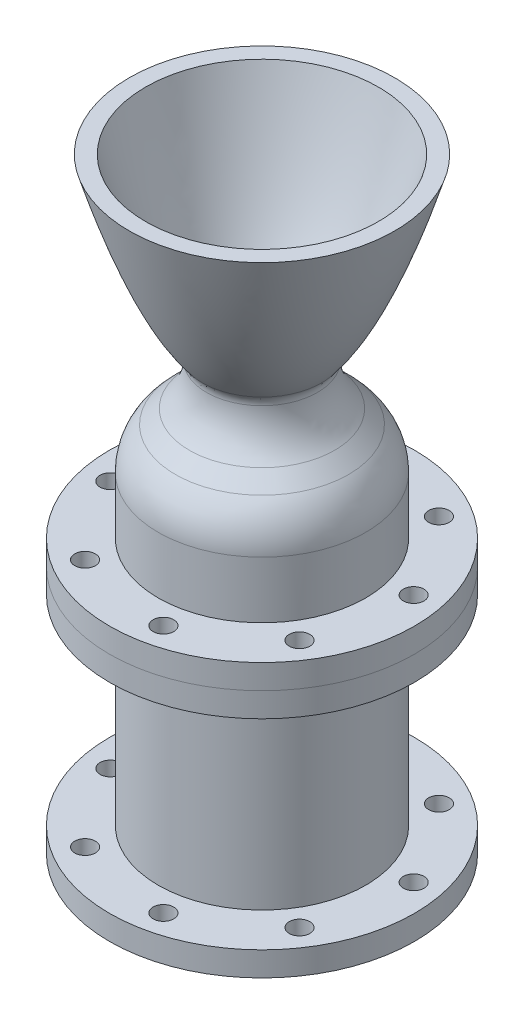
SolidWorks part; units mm, degrees
material "AISI 1020"
ref_plane "Front Plane" through (0, 0, 0) normal (0, 0, 1) x (1, 0, 0)
ref_plane "Top Plane" through (0, 0, 0) normal (0, 1, 0) x (1, 0, 0)
ref_plane "Right Plane" through (0, 0, 0) normal (1, 0, 0) x (0, 0, -1)
sketch "Sketch1" plane through (0, 0, 0) normal (0, 0, 1) x (1, 0, 0)
  line L0 (-0.0055, 165.816) -> (-0.0055, -134.6871) construction
  line L1 (71.7275, 109.9275) -> (81.7275, 109.9275)
  line L4 (53.8815, -59.7275) -> (53.8815, -262.9275)
  line L7 (63.8815, -59.761) -> (63.8815, -262.9447)
  line L8 (53.8815, -262.9275) -> (63.8815, -262.9447)
  spline S0 degree 2 poles (26.7953, 6.5094) (49.2614, 34.6361) (71.7275, 109.9275) knots 0 0 0 1 1 1 construction
  spline S1 degree 2 poles (26.7953, 6.5094) (49.2614, 34.6361) (71.7275, 109.9275) knots 0 0 0 1 1 1
  spline S2 degree 4 poles (24.1269, -0.7179) (24.126, -0.7018) (24.1243, -0.6738) (24.121, -0.6546) (24.115, -0.5166) (24.1058, -0.4369) (24.0994, -0.1066) (24.0979, 0.0018) (24.102, 0.2678) (24.1085, 0.4272) (24.1205, 0.6469) (24.1414, 0.9016) (24.1752, 1.2027) (24.2265, 1.5422) (24.2905, 1.8812) (24.3671, 2.2165) (24.4563, 2.5494) (24.5577, 2.8783) (24.6716, 3.2035) (24.7972, 3.5238) (24.9353, 3.8398) (25.0841, 4.1494) (25.246, 4.4549) (25.4165, 4.7515) (25.6025, 5.0459) (25.7918, 5.3257) (26.0044, 5.6109) (26.1789, 5.8331) (26.3663, 6.0501) (26.5046, 6.2088) (26.757, 6.4728) (26.837, 6.5526) (27.1016, 6.806) (27.1881, 6.8783) (27.2854, 6.9667) (27.3038, 6.9803) (27.3264, 7.0004) knots 0 0 0 0 0 0.005192 0.010384 0.020768 0.041536 0.082569 0.102427 0.122284 0.142142 0.162 0.201716 0.241431 0.281147 0.320863 0.360578 0.400294 0.44001 0.479725 0.519441 0.559156 0.598872 0.638588 0.678303 0.718019 0.757735 0.79745 0.837166 0.857024 0.876882 0.916597 0.958047 0.979024 0.989512 1 1 1 1 1 construction
  spline S3 degree 4 poles (24.0991, 0.0002) (24.0991, 0.0361) (24.0996, 0.1103) (24.102, 0.2678) (24.1085, 0.4272) (24.1205, 0.6469) (24.1414, 0.9016) (24.1752, 1.2027) (24.2265, 1.5422) (24.2905, 1.8812) (24.3671, 2.2165) (24.4563, 2.5494) (24.5577, 2.8783) (24.6716, 3.2035) (24.7972, 3.5238) (24.9353, 3.8398) (25.0841, 4.1494) (25.246, 4.4549) (25.4165, 4.7515) (25.6025, 5.0459) (25.7918, 5.3257) (26.0044, 5.6109) (26.1789, 5.8331) (26.3663, 6.0501) (26.5046, 6.2088) (26.6704, 6.3823) (26.7445, 6.4586) (26.7953, 6.5094) knots 0.082569 0.082569 0.082569 0.082569 0.082569 0.102427 0.122284 0.142142 0.162 0.201716 0.241431 0.281147 0.320863 0.360578 0.400294 0.44001 0.479725 0.519441 0.559156 0.598872 0.638588 0.678303 0.718019 0.757735 0.79745 0.837166 0.857024 0.876882 0.916597 0.916597 0.916597 0.916597 0.916597
  spline S4 degree 4 poles (24.2082, 2.808) (24.2014, 2.7166) (24.1882, 2.5518) (24.1642, 2.1754) (24.1352, 1.6881) (24.1148, 1.1018) (24.103, 0.6556) (24.0988, 0.1104) (24.0988, -0.0999) (24.102, -0.543) (24.1083, -0.824) (24.1178, -1.1947) (24.1304, -1.5133) (24.1462, -1.8618) (24.1652, -2.1935) (24.1928, -2.6179) (24.2323, -3.1219) (24.3033, -3.8798) (24.4231, -4.8863) (24.5995, -6.0566) (24.8509, -7.385) (25.1518, -8.7034) (25.5018, -10.0095) (25.9004, -11.3017) (26.3469, -12.5779) (26.841, -13.8367) (27.3817, -15.076) (27.9685, -16.2944) (28.6001, -17.4898) (29.2765, -18.6611) (29.9954, -19.8056) (30.758, -20.9237) (31.4592, -21.8743) (32.0887, -22.6733) (32.6241, -23.3203) (33.0723, -23.8398) (33.5085, -24.3297) (33.9358, -24.7883) (34.2456, -25.1137) (34.6121, -25.4859) (34.7661, -25.6398) (35.1509, -26.0187) (35.4776, -26.3286) (35.905, -26.7273) (36.2395, -27.0242) (36.5192, -27.2707) (36.6465, -27.3798) (36.7148, -27.4387) (36.7496, -27.4686) knots 0 0 0 0 0 0.010393 0.020785 0.041571 0.062104 0.072371 0.082638 0.092575 0.102512 0.112449 0.122387 0.132324 0.142261 0.152198 0.162135 0.18201 0.201884 0.241633 0.281382 0.32113 0.360879 0.400628 0.440377 0.480126 0.519874 0.559623 0.599372 0.639121 0.67887 0.718618 0.758367 0.798116 0.81799 0.837865 0.857739 0.877613 0.897488 0.907425 0.917362 0.927629 0.937896 0.958429 0.979215 0.989607 0.994804 1 1 1 1 1 construction
  spline S5 degree 4 poles (24.0991, 0.0002) (24.0991, -0.0704) (24.0996, -0.2134) (24.102, -0.543) (24.1083, -0.824) (24.1178, -1.1947) (24.1304, -1.5133) (24.1462, -1.8618) (24.1652, -2.1935) (24.1928, -2.6179) (24.2323, -3.1219) (24.3033, -3.8798) (24.4231, -4.8863) (24.5995, -6.0566) (24.8509, -7.385) (25.1518, -8.7034) (25.5018, -10.0095) (25.9004, -11.3017) (26.3469, -12.5779) (26.841, -13.8367) (27.3817, -15.076) (27.9685, -16.2944) (28.6001, -17.4898) (29.2765, -18.6611) (29.9954, -19.8056) (30.758, -20.9237) (31.4592, -21.8743) (32.0887, -22.6733) (32.6241, -23.3203) (33.0723, -23.8398) (33.5085, -24.3297) (33.9358, -24.7883) (34.2456, -25.1137) (34.5369, -25.4095) (34.6364, -25.5098) (34.6863, -25.5597) knots 0.082638 0.082638 0.082638 0.082638 0.082638 0.092575 0.102512 0.112449 0.122387 0.132324 0.142261 0.152198 0.162135 0.18201 0.201884 0.241633 0.281382 0.32113 0.360879 0.400628 0.440377 0.480126 0.519874 0.559623 0.599372 0.639121 0.67887 0.718618 0.758367 0.798116 0.81799 0.837865 0.857739 0.877613 0.897488 0.907425 0.917362 0.917362 0.917362 0.917362 0.917362
  spline S6 degree 1 poles (34.6863, -25.5597) (43.2939, -34.1673) knots 0 0 1 1 construction
  spline S7 degree 1 poles (34.6863, -25.5597) (43.2939, -34.1673) knots 0 0 1 1
  spline S8 degree 4 poles (53.7724, -62.5352) (53.7792, -62.4464) (53.7924, -62.2737) (53.8104, -62.0016) (53.8309, -61.6599) (53.848, -61.2921) (53.8616, -60.9658) (53.8717, -60.5752) (53.8784, -60.2939) (53.8818, -59.8332) (53.8818, -59.6304) (53.8786, -59.1816) (53.8723, -58.9048) (53.8628, -58.5326) (53.8502, -58.2128) (53.8304, -57.7816) (53.8004, -57.281) (53.7562, -56.688) (53.6773, -55.8485) (53.5774, -55.0082) (53.4567, -54.1724) (53.2868, -53.1724) (53.0921, -52.1774) (52.8664, -51.1885) (52.61, -50.2075) (52.3293, -49.2331) (52.0243, -48.266) (51.6335, -47.1491) (51.1395, -45.8904) (50.5987, -44.651) (50.0121, -43.4327) (49.3801, -42.2371) (48.7041, -41.0662) (47.9845, -39.921) (47.2231, -38.8041) (46.5199, -37.8515) (45.8935, -37.0557) (45.3528, -36.4034) (44.9151, -35.8942) (44.5148, -35.447) (44.1815, -35.0846) (43.8739, -34.7603) (43.6741, -34.5515) (43.3653, -34.2383) (43.2159, -34.0889) (42.8277, -33.7066) (42.5041, -33.3998) (42.0741, -32.9986) (41.7412, -32.7033) (41.4607, -32.4559) (41.3338, -32.3472) (41.2653, -32.2883) (41.2305, -32.2583) knots 0 0 0 0 0 0.010393 0.020785 0.031178 0.041571 0.051838 0.062104 0.072371 0.082638 0.092575 0.102512 0.112449 0.122387 0.132324 0.142261 0.162135 0.18201 0.201884 0.241633 0.261507 0.281382 0.32113 0.360879 0.380754 0.400628 0.440377 0.480126 0.519874 0.559623 0.599372 0.639121 0.67887 0.718618 0.758367 0.798116 0.81799 0.837865 0.857739 0.877613 0.887551 0.897488 0.907425 0.917362 0.927629 0.937896 0.958429 0.979215 0.989607 0.994804 1 1 1 1 1 construction
  spline S9 degree 4 poles (53.8815, -59.7275) (53.8815, -59.657) (53.881, -59.5154) (53.8786, -59.1816) (53.8723, -58.9048) (53.8628, -58.5326) (53.8502, -58.2128) (53.8304, -57.7816) (53.8004, -57.281) (53.7562, -56.688) (53.6773, -55.8485) (53.5774, -55.0082) (53.4567, -54.1724) (53.2868, -53.1724) (53.0921, -52.1774) (52.8664, -51.1885) (52.61, -50.2075) (52.3293, -49.2331) (52.0243, -48.266) (51.6335, -47.1491) (51.1395, -45.8904) (50.5987, -44.651) (50.0121, -43.4327) (49.3801, -42.2371) (48.7041, -41.0662) (47.9845, -39.921) (47.2231, -38.8041) (46.5199, -37.8515) (45.8935, -37.0557) (45.3528, -36.4034) (44.9151, -35.8942) (44.5148, -35.447) (44.1815, -35.0846) (43.8739, -34.7603) (43.6741, -34.5515) (43.4444, -34.3185) (43.3438, -34.2172) (43.2939, -34.1673) knots 0.082638 0.082638 0.082638 0.082638 0.082638 0.092575 0.102512 0.112449 0.122387 0.132324 0.142261 0.162135 0.18201 0.201884 0.241633 0.261507 0.281382 0.32113 0.360879 0.380754 0.400628 0.440377 0.480126 0.519874 0.559623 0.599372 0.639121 0.67887 0.718618 0.758367 0.798116 0.81799 0.837865 0.857739 0.877613 0.887551 0.897488 0.907425 0.917362 0.917362 0.917362 0.917362 0.917362
  spline S10 degree 2 poles (36.8348, 6.4922) (59.2902, 34.6275) (81.7275, 109.9275) knots 0 0 0 1 1 1 construction
  spline S11 degree 2 poles (36.8348, 6.4922) (59.2902, 34.6275) (81.7275, 109.9275) knots 0 0 0 1 1 1
  spline S12 degree 4 poles (34.1664, -0.7351) (34.1655, -0.719) (34.1638, -0.691) (34.1605, -0.6718) (34.1546, -0.5338) (34.1454, -0.4541) (34.1389, -0.1238) (34.1375, -0.0154) (34.1416, 0.2506) (34.148, 0.4101) (34.1601, 0.6298) (34.181, 0.8844) (34.2147, 1.1855) (34.266, 1.525) (34.3301, 1.864) (34.4067, 2.1993) (34.4959, 2.5322) (34.5973, 2.8611) (34.7112, 3.1863) (34.8367, 3.5066) (34.9748, 3.8227) (35.1236, 4.1323) (35.2856, 4.4378) (35.456, 4.7343) (35.6421, 5.0287) (35.8313, 5.3085) (36.0439, 5.5937) (36.2184, 5.8159) (36.4059, 6.0329) (36.5441, 6.1916) (36.7965, 6.4556) (36.8765, 6.5354) (37.1411, 6.7888) (37.2276, 6.8611) (37.3249, 6.9496) (37.3433, 6.9632) (37.3659, 6.9832) knots 0 0 0 0 0 0.005192 0.010384 0.020768 0.041536 0.082569 0.102427 0.122284 0.142142 0.162 0.201716 0.241431 0.281147 0.320863 0.360578 0.400294 0.44001 0.479725 0.519441 0.559156 0.598872 0.638588 0.678303 0.718019 0.757735 0.79745 0.837166 0.857024 0.876882 0.916597 0.958047 0.979024 0.989512 1 1 1 1 1 construction
  spline S13 degree 4 poles (34.1386, -0.017) (34.1386, 0.0189) (34.1391, 0.0931) (34.1416, 0.2506) (34.148, 0.4101) (34.1601, 0.6298) (34.181, 0.8844) (34.2147, 1.1855) (34.266, 1.525) (34.3301, 1.864) (34.4067, 2.1993) (34.4959, 2.5322) (34.5973, 2.8611) (34.7112, 3.1863) (34.8367, 3.5066) (34.9748, 3.8227) (35.1236, 4.1323) (35.2856, 4.4378) (35.456, 4.7343) (35.6421, 5.0287) (35.8313, 5.3085) (36.0439, 5.5937) (36.2184, 5.8159) (36.4059, 6.0329) (36.5441, 6.1916) (36.71, 6.3651) (36.7841, 6.4415) (36.8348, 6.4922) knots 0.082569 0.082569 0.082569 0.082569 0.082569 0.102427 0.122284 0.142142 0.162 0.201716 0.241431 0.281147 0.320863 0.360578 0.400294 0.44001 0.479725 0.519441 0.559156 0.598872 0.638588 0.678303 0.718019 0.757735 0.79745 0.837166 0.857024 0.876882 0.916597 0.916597 0.916597 0.916597 0.916597
  spline S14 degree 4 poles (34.2478, 2.7908) (34.2409, 2.6994) (34.2278, 2.5346) (34.2038, 2.1582) (34.1748, 1.6709) (34.1544, 1.0846) (34.1425, 0.6384) (34.1384, 0.0932) (34.1383, -0.1171) (34.1415, -0.5602) (34.1478, -0.8412) (34.1573, -1.2118) (34.17, -1.5304) (34.1858, -1.8789) (34.2047, -2.2107) (34.2324, -2.6351) (34.2718, -3.139) (34.3428, -3.897) (34.4627, -4.9035) (34.639, -6.0737) (34.8904, -7.4022) (35.1913, -8.7206) (35.5413, -10.0266) (35.9399, -11.3188) (36.3865, -12.5951) (36.8805, -13.8539) (37.4212, -15.0932) (38.008, -16.3116) (38.6397, -17.5069) (39.3161, -18.6783) (40.035, -19.8228) (40.7976, -20.9409) (41.4987, -21.8914) (42.1283, -22.6905) (42.6637, -23.3374) (43.1118, -23.857) (43.548, -24.3468) (43.9754, -24.8055) (44.2851, -25.1309) (44.6516, -25.5031) (44.8056, -25.657) (45.1904, -26.0359) (45.5171, -26.3458) (45.9446, -26.7444) (46.2791, -27.0414) (46.5587, -27.2879) (46.686, -27.397) (46.7544, -27.4558) (46.7891, -27.4857) knots 0 0 0 0 0 0.010393 0.020785 0.041571 0.062104 0.072371 0.082638 0.092575 0.102512 0.112449 0.122387 0.132324 0.142261 0.152198 0.162135 0.18201 0.201884 0.241633 0.281382 0.32113 0.360879 0.400628 0.440377 0.480126 0.519874 0.559623 0.599372 0.639121 0.67887 0.718618 0.758367 0.798116 0.81799 0.837865 0.857739 0.877613 0.897488 0.907425 0.917362 0.927629 0.937896 0.958429 0.979215 0.989607 0.994804 1 1 1 1 1 construction
  spline S15 degree 4 poles (34.1386, -0.017) (34.1386, -0.0875) (34.1391, -0.2306) (34.1415, -0.5602) (34.1478, -0.8412) (34.1573, -1.2118) (34.17, -1.5304) (34.1858, -1.8789) (34.2047, -2.2107) (34.2324, -2.6351) (34.2718, -3.139) (34.3428, -3.897) (34.4627, -4.9035) (34.639, -6.0737) (34.8904, -7.4022) (35.1913, -8.7206) (35.5413, -10.0266) (35.9399, -11.3188) (36.3865, -12.5951) (36.8805, -13.8539) (37.4212, -15.0932) (38.008, -16.3116) (38.6397, -17.5069) (39.3161, -18.6783) (40.035, -19.8228) (40.7976, -20.9409) (41.4987, -21.8914) (42.1283, -22.6905) (42.6637, -23.3374) (43.1118, -23.857) (43.548, -24.3468) (43.9754, -24.8055) (44.2851, -25.1309) (44.5764, -25.4267) (44.676, -25.527) (44.7258, -25.5768) knots 0.082638 0.082638 0.082638 0.082638 0.082638 0.092575 0.102512 0.112449 0.122387 0.132324 0.142261 0.152198 0.162135 0.18201 0.201884 0.241633 0.281382 0.32113 0.360879 0.400628 0.440377 0.480126 0.519874 0.559623 0.599372 0.639121 0.67887 0.718618 0.758367 0.798116 0.81799 0.837865 0.857739 0.877613 0.897488 0.907425 0.917362 0.917362 0.917362 0.917362 0.917362
  spline S16 degree 1 poles (44.7258, -25.5768) (53.3335, -34.1845) knots 0 0 1 1 construction
  spline S17 degree 1 poles (44.7258, -25.5768) (53.3335, -34.1845) knots 0 0 1 1
  spline S18 degree 4 poles (63.768, -62.5686) (63.775, -62.4798) (63.7884, -62.3071) (63.8069, -62.035) (63.8279, -61.6934) (63.8456, -61.3255) (63.8596, -60.9993) (63.8704, -60.6087) (63.8776, -60.3275) (63.8816, -59.8667) (63.882, -59.6639) (63.8795, -59.2151) (63.8736, -58.9383) (63.8647, -58.5661) (63.8525, -58.2463) (63.8334, -57.815) (63.8042, -57.3144) (63.7609, -56.7213) (63.6833, -55.8817) (63.5847, -55.0412) (63.4653, -54.2053) (63.2969, -53.205) (63.1037, -52.2097) (62.8796, -51.2205) (62.6247, -50.239) (62.3455, -49.2642) (62.0421, -48.2966) (61.653, -47.1792) (61.1609, -45.9197) (60.6221, -44.6794) (60.0373, -43.4603) (59.4072, -42.2637) (58.733, -41.0917) (58.0151, -39.9454) (57.2555, -38.8273) (56.5537, -37.8736) (55.9286, -37.0769) (55.3889, -36.4237) (54.952, -35.9139) (54.5523, -35.466) (54.2196, -35.1032) (53.9125, -34.7784) (53.713, -34.5693) (53.4047, -34.2555) (53.2556, -34.106) (52.8679, -33.7231) (52.5448, -33.4157) (52.1154, -33.0139) (51.783, -32.7181) (51.5028, -32.4703) (51.3761, -32.3614) (51.3078, -32.3023) (51.273, -32.2723) knots 0 0 0 0 0 0.010393 0.020785 0.031178 0.041571 0.051838 0.062104 0.072371 0.082638 0.092575 0.102512 0.112449 0.122387 0.132324 0.142261 0.162135 0.18201 0.201884 0.241633 0.261507 0.281382 0.32113 0.360879 0.380754 0.400628 0.440377 0.480126 0.519874 0.559623 0.599372 0.639121 0.67887 0.718618 0.758367 0.798116 0.81799 0.837865 0.857739 0.877613 0.887551 0.897488 0.907425 0.917362 0.927629 0.937896 0.958429 0.979215 0.989607 0.994804 1 1 1 1 1 construction
  spline S19 degree 4 poles (63.8815, -59.761) (63.8816, -59.6905) (63.8813, -59.5489) (63.8795, -59.2151) (63.8736, -58.9383) (63.8647, -58.5661) (63.8525, -58.2463) (63.8334, -57.815) (63.8042, -57.3144) (63.7609, -56.7213) (63.6833, -55.8817) (63.5847, -55.0412) (63.4653, -54.2053) (63.2969, -53.205) (63.1037, -52.2097) (62.8796, -51.2205) (62.6247, -50.239) (62.3455, -49.2642) (62.0421, -48.2966) (61.653, -47.1792) (61.1609, -45.9197) (60.6221, -44.6794) (60.0373, -43.4603) (59.4072, -42.2637) (58.733, -41.0917) (58.0151, -39.9454) (57.2555, -38.8273) (56.5537, -37.8736) (55.9286, -37.0769) (55.3889, -36.4237) (54.952, -35.9139) (54.5523, -35.466) (54.2196, -35.1032) (53.9125, -34.7784) (53.713, -34.5693) (53.4837, -34.3359) (53.3832, -34.2344) (53.3335, -34.1845) knots 0.082638 0.082638 0.082638 0.082638 0.082638 0.092575 0.102512 0.112449 0.122387 0.132324 0.142261 0.162135 0.18201 0.201884 0.241633 0.261507 0.281382 0.32113 0.360879 0.380754 0.400628 0.440377 0.480126 0.519874 0.559623 0.599372 0.639121 0.67887 0.718618 0.758367 0.798116 0.81799 0.837865 0.857739 0.877613 0.887551 0.897488 0.907425 0.917362 0.917362 0.917362 0.917362 0.917362
  dimension "D1" = 24.1046
  dimension "D2" = 53.8871
  dimension "D3" = 203.2
  dimension "D4" = 10
  dimension "D5" = 10
  dimension "D7" = 24.0991
  dimension "D8" = 26.7953
  dimension "D9" = 34.6863
  dimension "D10" = 0.0002
revolve "Revolve2" add sketch "Sketch1" angle 360 about L0
ref_plane "Plane1" through (0, -262.9447, 0) normal (0, 1, 0) x (1, 0, 0)
ref_plane "Plane3" through (0, -109.7447, 0) normal (0, 1, 0) x (1, 0, 0)
sketch "Sketch2" plane through (0, -109.7447, 0) normal (0, 1, 0) x (1, 0, 0)
  circle A0 centre (0, 0) radius 63.8815
  circle A2 centre (0, 0) radius 93.8815
  dimension "D1" = 30
extrude "Boss-Extrude1" add sketch "Sketch2" along normal mid plane 30
sketch "Sketch3" plane through (0, -262.9447, 0) normal (0, 1, 0) x (1, 0, 0)
  circle A0 centre (0, 0) radius 63.8815
  circle A1 centre (0, 0) radius 93.8815
extrude "Boss-Extrude2" add sketch "Sketch3" along normal blind 15
hole_wizard "1/2 (0.5) Diameter Hole1" positions "Sketch7" profile "Sketch6" hole size "1/2" standard "ANSI Inch"
sketch "Sketch7" plane through (0, -262.9447, 0) normal (0, -1, 0) x (-1, 0, 0)
  point P0 (42.9291, -66.0342)
  point P1 (48.0354, -63.4199)
  point P2 (59.8817, -51.8127)
  point P3 (42.9291, -66.0342)
sketch "Sketch6" plane through (-42.9291, -262.9447, 66.0342) normal (1, 0, 0) x (0, 0, -1)
  line L0 (0, 0) -> (0, 203.8155)
  line L1 (0, 203.8155) -> (6.35, 200)
  line L2 (6.35, 200) -> (6.35, 0)
  line L5 (6.35, 0) -> (0, 0)
  line L10 (0, 203.8155) -> (-6.35, 200) construction
  line L11 (0, -6.35) -> (0, 107.95) construction
  dimension "Hole Dia." = 12.7
  dimension "Hole Depth" = 200
  dimension "Drill Angle" = 118
sketch "Sketch8" plane through (0, -262.9447, 0) normal (0, -1, 0) x (1, 0, 0)
  circle A0 centre (0, 0) radius 93.8815 construction
  circle A1 centre (0, 0) radius 78.8815 construction
  point P4 (0, 0)
  dimension "D1" = 15
sketch "Sketch9" plane through (0, 0, 0) normal (0, 0, 1) x (1, 0, 0)
  line L0 (0, -287.1234) -> (0, 68.3757) construction
sketch "Sketch10" plane through (0, -262.9447, 0) normal (0, -1, 0) x (1, 0, 0)
  line L0 (0, 0) -> (-20.787, 75.4962) construction
pattern_circular "CirPattern1" count 8 over 360 about axis through (0, 0, 0) along (0, 1, 0) of "1/2 (0.5) Diameter Hole1"
split "Split1" trim tools "Plane3" bodies to split 105 resulting bodies 106 107
